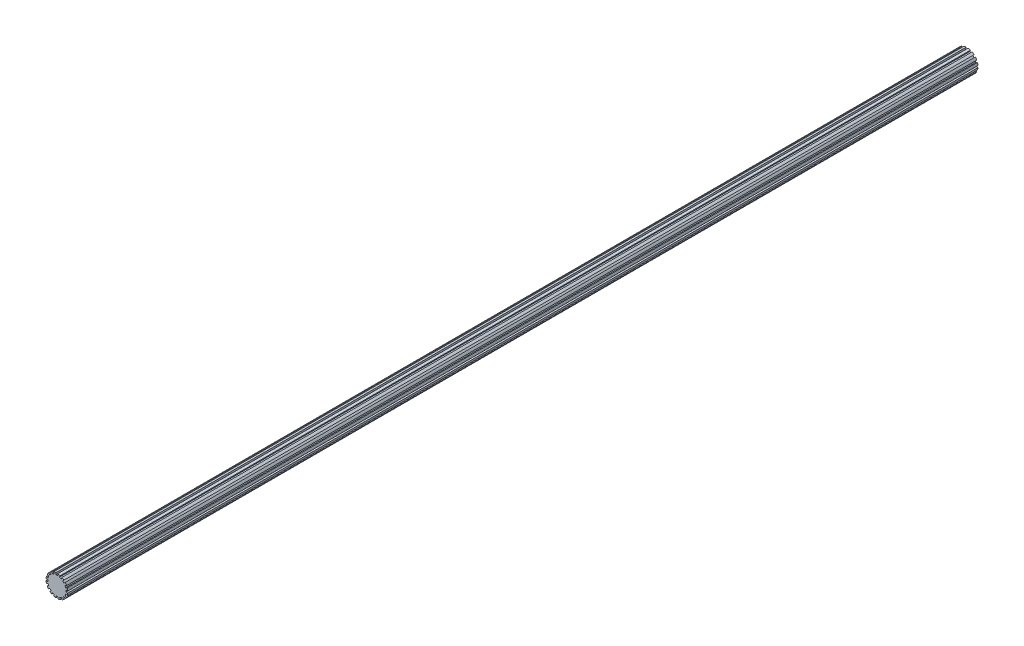
SolidWorks part; units mm, degrees
ref_plane "Front Plane" through (0, 0, 0) normal (0, 0, 1) x (1, 0, 0)
ref_plane "Top Plane" through (0, 0, 0) normal (0, 1, 0) x (1, 0, 0)
ref_plane "Right Plane" through (0, 0, 0) normal (1, 0, 0) x (0, 0, -1)
sketch "Sketch1" plane through (0, 0, 0) normal (0, 0, 1) x (1, 0, 0)
  circle A0 centre (0, 0) radius 3
extrude "Boss-Extrude1" add sketch "Sketch1" along normal blind 250
sketch "Sketch2" plane through (0, 0, 250) normal (0, 0, 1) x (1, 0, 0)
  line L0 (0, 3) -> (0, 2.5024) construction
  line L1 (-0.251, 2.5024) -> (0.251, 2.5024)
  line L2 (0.251, 2.5024) -> (0.251, 2.9895)
  line L3 (-0.251, 2.5024) -> (-0.251, 2.9895)
  line L4 (-0.251, 2.9895) -> (-0.251, 3.1233)
  line L5 (-0.251, 3.1233) -> (0.251, 3.1233)
  line L6 (0.251, 3.1233) -> (0.251, 2.9895)
  line L7 (1.4271, 2.7895) -> (1.3759, 2.6659)
  line L8 (1.1895, 2.2159) -> (1.3759, 2.6659)
  line L9 (0.7257, 2.408) -> (1.1895, 2.2159)
  line L10 (0.7257, 2.408) -> (0.9121, 2.858)
  line L11 (0.9121, 2.858) -> (0.9633, 2.9816)
  line L12 (0.9633, 2.9816) -> (1.4271, 2.7895)
  line L13 (2.386, 2.031) -> (2.2914, 1.9364)
  line L14 (1.947, 1.592) -> (2.2914, 1.9364)
  line L15 (1.592, 1.947) -> (1.947, 1.592)
  line L16 (1.592, 1.947) -> (1.9364, 2.2914)
  line L17 (1.9364, 2.2914) -> (2.031, 2.386)
  line L18 (2.031, 2.386) -> (2.386, 2.031)
  line L19 (2.9816, 0.9633) -> (2.858, 0.9121)
  line L20 (2.408, 0.7257) -> (2.858, 0.9121)
  line L21 (2.2159, 1.1895) -> (2.408, 0.7257)
  line L22 (2.2159, 1.1895) -> (2.6659, 1.3759)
  line L23 (2.6659, 1.3759) -> (2.7895, 1.4271)
  line L24 (2.7895, 1.4271) -> (2.9816, 0.9633)
  line L25 (3.1233, -0.251) -> (2.9895, -0.251)
  line L26 (2.5024, -0.251) -> (2.9895, -0.251)
  line L27 (2.5024, 0.251) -> (2.5024, -0.251)
  line L28 (2.5024, 0.251) -> (2.9895, 0.251)
  line L29 (2.9895, 0.251) -> (3.1233, 0.251)
  line L30 (3.1233, 0.251) -> (3.1233, -0.251)
  line L31 (2.7895, -1.4271) -> (2.6659, -1.3759)
  line L32 (2.2159, -1.1895) -> (2.6659, -1.3759)
  line L33 (2.408, -0.7257) -> (2.2159, -1.1895)
  line L34 (2.408, -0.7257) -> (2.858, -0.9121)
  line L35 (2.858, -0.9121) -> (2.9816, -0.9633)
  line L36 (2.9816, -0.9633) -> (2.7895, -1.4271)
  line L37 (2.031, -2.386) -> (1.9364, -2.2914)
  line L38 (1.592, -1.947) -> (1.9364, -2.2914)
  line L39 (1.947, -1.592) -> (1.592, -1.947)
  line L40 (1.947, -1.592) -> (2.2914, -1.9364)
  line L41 (2.2914, -1.9364) -> (2.386, -2.031)
  line L42 (2.386, -2.031) -> (2.031, -2.386)
  line L43 (0.9633, -2.9816) -> (0.9121, -2.858)
  line L44 (0.7257, -2.408) -> (0.9121, -2.858)
  line L45 (1.1895, -2.2159) -> (0.7257, -2.408)
  line L46 (1.1895, -2.2159) -> (1.3759, -2.6659)
  line L47 (1.3759, -2.6659) -> (1.4271, -2.7895)
  line L48 (1.4271, -2.7895) -> (0.9633, -2.9816)
  line L49 (-0.251, -3.1233) -> (-0.251, -2.9895)
  line L50 (-0.251, -2.5024) -> (-0.251, -2.9895)
  line L51 (0.251, -2.5024) -> (-0.251, -2.5024)
  line L52 (0.251, -2.5024) -> (0.251, -2.9895)
  line L53 (0.251, -2.9895) -> (0.251, -3.1233)
  line L54 (0.251, -3.1233) -> (-0.251, -3.1233)
  line L55 (-1.4271, -2.7895) -> (-1.3759, -2.6659)
  line L56 (-1.1895, -2.2159) -> (-1.3759, -2.6659)
  line L57 (-0.7257, -2.408) -> (-1.1895, -2.2159)
  line L58 (-0.7257, -2.408) -> (-0.9121, -2.858)
  line L59 (-0.9121, -2.858) -> (-0.9633, -2.9816)
  line L60 (-0.9633, -2.9816) -> (-1.4271, -2.7895)
  line L61 (-2.386, -2.031) -> (-2.2914, -1.9364)
  line L62 (-1.947, -1.592) -> (-2.2914, -1.9364)
  line L63 (-1.592, -1.947) -> (-1.947, -1.592)
  line L64 (-1.592, -1.947) -> (-1.9364, -2.2914)
  line L65 (-1.9364, -2.2914) -> (-2.031, -2.386)
  line L66 (-2.031, -2.386) -> (-2.386, -2.031)
  line L67 (-2.9816, -0.9633) -> (-2.858, -0.9121)
  line L68 (-2.408, -0.7257) -> (-2.858, -0.9121)
  line L69 (-2.2159, -1.1895) -> (-2.408, -0.7257)
  line L70 (-2.2159, -1.1895) -> (-2.6659, -1.3759)
  line L71 (-2.6659, -1.3759) -> (-2.7895, -1.4271)
  line L72 (-2.7895, -1.4271) -> (-2.9816, -0.9633)
  line L73 (-3.1233, 0.251) -> (-2.9895, 0.251)
  line L74 (-2.5024, 0.251) -> (-2.9895, 0.251)
  line L75 (-2.5024, -0.251) -> (-2.5024, 0.251)
  line L76 (-2.5024, -0.251) -> (-2.9895, -0.251)
  line L77 (-2.9895, -0.251) -> (-3.1233, -0.251)
  line L78 (-3.1233, -0.251) -> (-3.1233, 0.251)
  line L79 (-2.7895, 1.4271) -> (-2.6659, 1.3759)
  line L80 (-2.2159, 1.1895) -> (-2.6659, 1.3759)
  line L81 (-2.408, 0.7257) -> (-2.2159, 1.1895)
  line L82 (-2.408, 0.7257) -> (-2.858, 0.9121)
  line L83 (-2.858, 0.9121) -> (-2.9816, 0.9633)
  line L84 (-2.9816, 0.9633) -> (-2.7895, 1.4271)
  line L85 (-2.031, 2.386) -> (-1.9364, 2.2914)
  line L86 (-1.592, 1.947) -> (-1.9364, 2.2914)
  line L87 (-1.947, 1.592) -> (-1.592, 1.947)
  line L88 (-1.947, 1.592) -> (-2.2914, 1.9364)
  line L89 (-2.2914, 1.9364) -> (-2.386, 2.031)
  line L90 (-2.386, 2.031) -> (-2.031, 2.386)
  line L91 (-0.9633, 2.9816) -> (-0.9121, 2.858)
  line L92 (-0.7257, 2.408) -> (-0.9121, 2.858)
  line L93 (-1.1895, 2.2159) -> (-0.7257, 2.408)
  line L94 (-1.1895, 2.2159) -> (-1.3759, 2.6659)
  line L95 (-1.3759, 2.6659) -> (-1.4271, 2.7895)
  line L96 (-1.4271, 2.7895) -> (-0.9633, 2.9816)
  circle A0 centre (0, 0) radius 3
  point P8 (0, 2.5024)
  circle M14 centre (0, 0) radius 3
  dimension "D1" = 16
extrude "Cut-Extrude2" cut sketch "Sketch2" against normal through all contours L22 L21 L20 M14 | L16 L15 L14 M14 | L0 L1 L2 M14 | L0 A0 L3 L1 | L94 L93 L92 M14 | L88 L87 L86 M14 | L82 L81 L80 M14 | L76 L75 L74 M14 | L70 L69 L68 M14 | L64 L63 L62 M14 | L58 L57 L56 M14 | L52 L51 L50 M14 | L46 L45 L44 M14 | L40 L39 L38 M14 | L34 L33 L32 M14 | L28 L27 L26 M14 | L10 L9 L8 M14
